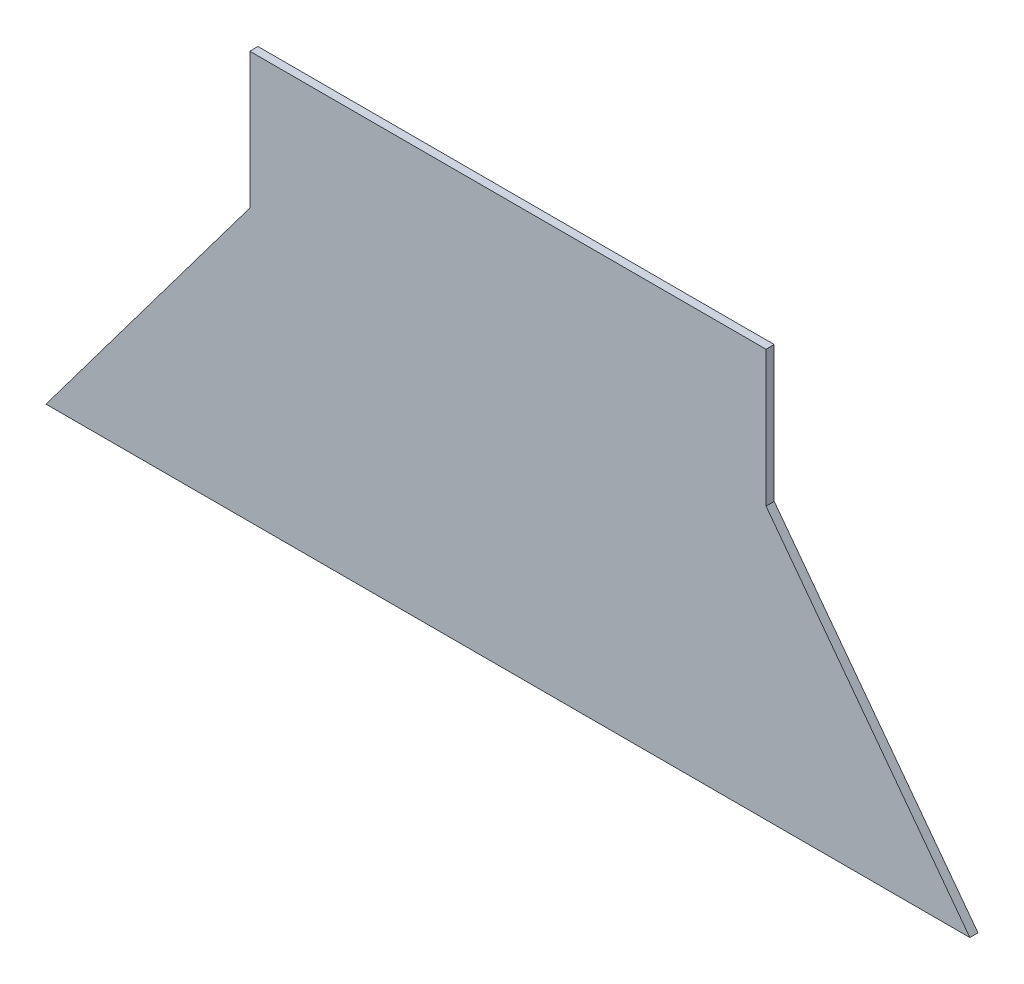
SolidWorks part; units mm, degrees
ref_plane "Plano frontal" through (0, 0, 0) normal (0, 0, 1) x (1, 0, 0)
ref_plane "Plano superior" through (0, 0, 0) normal (0, 1, 0) x (1, 0, 0)
ref_plane "Plano direito" through (0, 0, 0) normal (1, 0, 0) x (0, 0, -1)
sketch "Esboço1" plane through (0, 0, 0) normal (0, 0, 1) x (1, 0, 0)
  line L0 (0, 0) -> (150, 200)
  line L2 (530, 200) -> (680, 0)
  line L3 (680, 0) -> (0, 0)
  line L4 (340, 300) -> (340, 0) construction
  line L5 (150, 200) -> (150, 300)
  line L6 (150, 300) -> (530, 300)
  line L7 (530, 300) -> (530, 200)
  point P7 (340, 375.4076)
  point P10 (340, 370.3395)
  point P11 (150, 200)
  point P12 (0, 0)
  dimension "D1" = 680
  dimension "D2" = 380
  dimension "D3" = 200
  dimension "D4" = 100
extrude "Ressalto-extrusão1" add sketch "Esboço1" along normal blind 6
